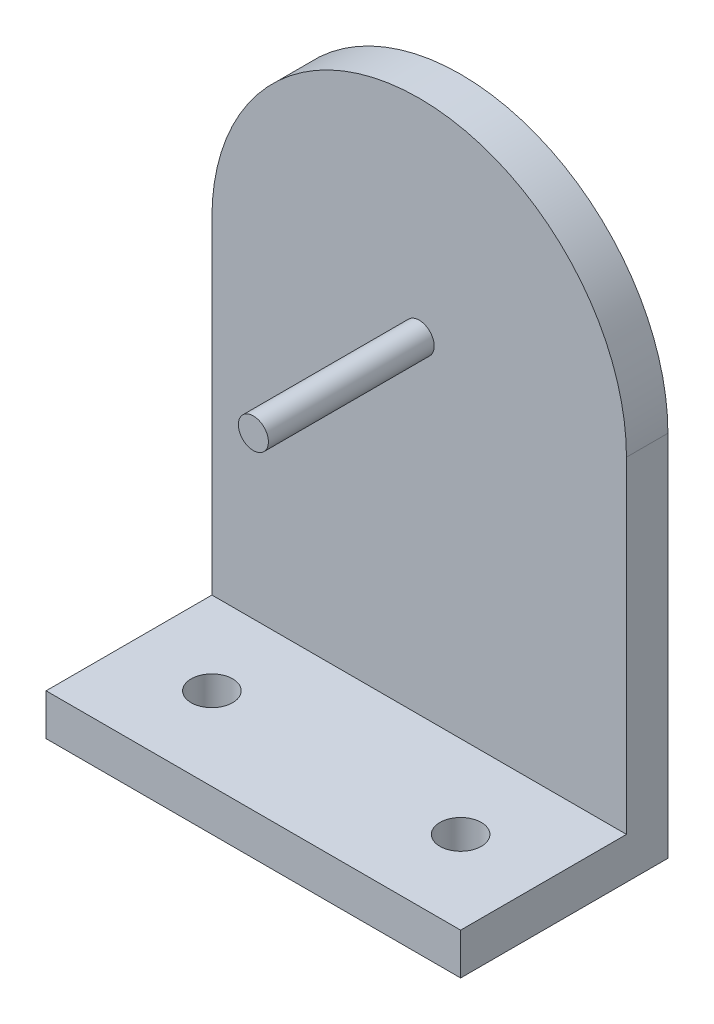
SolidWorks part; units mm, degrees
ref_plane "Front Plane" through (0, 0, 0) normal (0, 0, 1) x (1, 0, 0)
ref_plane "Top Plane" through (0, 0, 0) normal (0, 1, 0) x (1, 0, 0)
ref_plane "Right Plane" through (0, 0, 0) normal (1, 0, 0) x (0, 0, -1)
sketch "Sketch1" plane through (0, 0, 0) normal (0, 0, 1) x (1, 0, 0)
  line L1 (-15.875, 0) -> (15.875, 0)
  line L2 (-15.875, 0) -> (-15.875, -28.194)
  line L3 (-15.875, -28.194) -> (15.875, -28.194)
  line L4 (15.875, 0) -> (15.875, -28.194)
  circle A0 centre (0, 0) radius 15.875
  arc A2 (-15.875, 0) -> (15.875, 0) centre (0, 0) ccw
  dimension "D1" = 31.75
  dimension "D2" = 28.194
extrude "Boss-Extrude1" add sketch "Sketch1" along normal blind 3.175
sketch "Sketch4" plane through (0, 0, 3.175) normal (0, 0, 1) x (1, 0, 0)
  line L0 (15.875, 0) -> (15.875, -28.194) construction
  line L1 (-15.875, -28.194) -> (15.875, -28.194)
  line L2 (-15.875, -28.194) -> (-15.875, -25.019)
  line L3 (-15.875, -25.019) -> (15.875, -25.019)
  line L4 (15.875, -28.194) -> (15.875, -25.019)
  dimension "D1" = 3.175
extrude "Boss-Extrude2" add sketch "Sketch4" along normal blind 12.7
sketch "Sketch5" plane through (0, -25.019, 0) normal (0, 1, 0) x (1, 0, 0)
  line L0 (-15.875, -9.525) -> (15.875, -9.525) construction
  line L1 (-15.875, -15.875) -> (-15.875, -3.175) construction
  line L2 (15.875, -15.875) -> (15.875, -3.175) construction
  line L3 (0, -3.175) -> (0, -15.875) construction
  line L4 (15.875, -3.175) -> (-15.875, -3.175) construction
  line L5 (15.875, -15.875) -> (-15.875, -15.875) construction
  circle A0 centre (-9.525, -9.525) radius 1.5875
  circle A1 centre (9.525, -9.525) radius 1.5875
  dimension "D1" = 3.175
  dimension "D2" = 9.525
extrude "Cut-Extrude2" cut sketch "Sketch5" against normal through all
sketch "Sketch6" plane through (0, 0, 3.175) normal (0, 0, 1) x (1, 0, 0)
  circle A0 centre (0, 0) radius 1.15
  dimension "D1" = 2.3
extrude "Boss-Extrude3" add sketch "Sketch6" along normal through all
